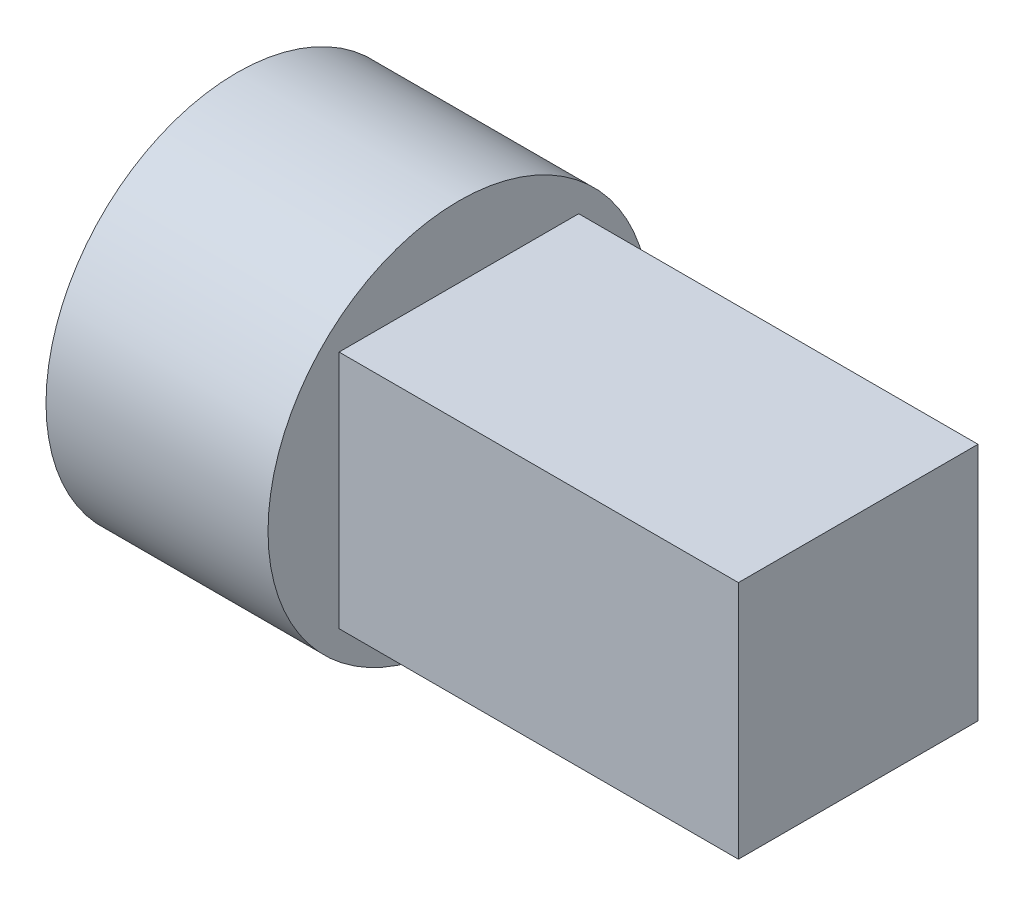
SolidWorks part; units mm, degrees
ref_plane "Front Plane" through (0, 0, 0) normal (0, 0, 1) x (1, 0, 0)
ref_plane "Top Plane" through (0, 0, 0) normal (0, 1, 0) x (1, 0, 0)
ref_plane "Right Plane" through (0, 0, 0) normal (1, 0, 0) x (0, 0, -1)
sketch "Sketch1" plane through (0, 0, 0) normal (1, 0, 0) x (0, 0, -1)
  circle A0 centre (0, 0) radius 4.78
  dimension "D1" = 9.56
extrude "Boss-Extrude1" add sketch "Sketch1" along normal mid plane 5.56
sketch "Sketch2" plane through (2.78, 0, 0) normal (1, 0, 0) x (0, 0, -1)
  line L1 (-3, 3) -> (3, 3)
  line L2 (-3, 3) -> (-3, -3)
  line L3 (-3, -3) -> (3, -3)
  line L4 (3, 3) -> (3, -3)
  line L5 (-3, 3) -> (3, -3) construction
  line L6 (-3, -3) -> (3, 3) construction
  point P0 (0, 0)
  dimension "D1" = 6
extrude "Boss-Extrude2" add sketch "Sketch2" along normal blind 10
